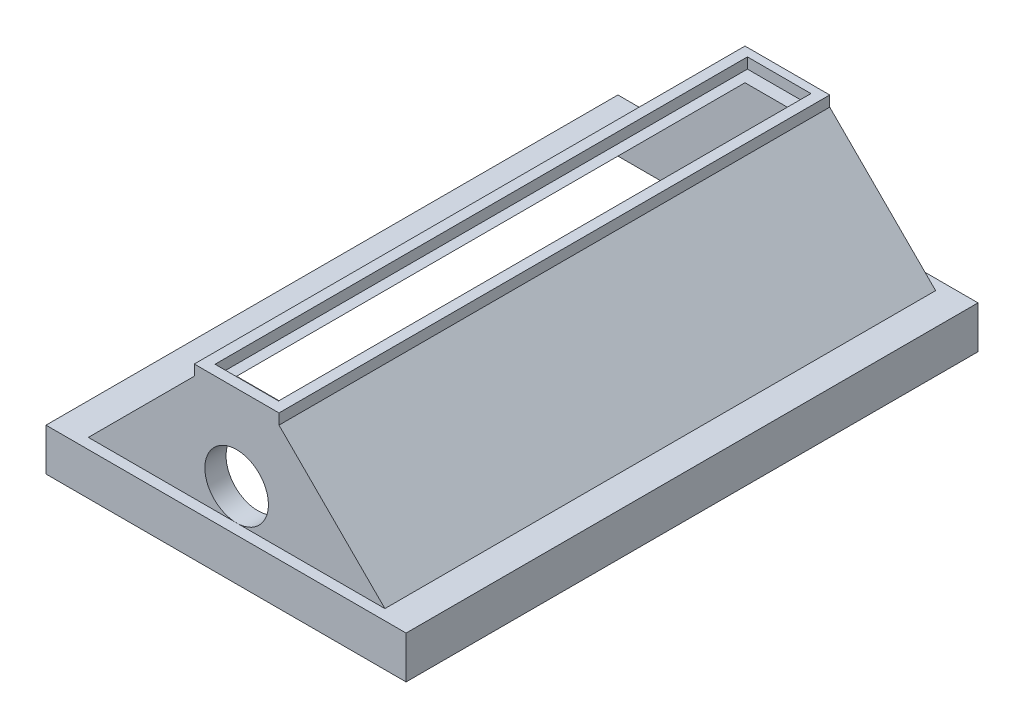
SolidWorks part; units mm, degrees
ref_plane "Front Plane" through (0, 0, 0) normal (0, 0, 1) x (1, 0, 0)
ref_plane "Top Plane" through (0, 0, 0) normal (0, 1, 0) x (1, 0, 0)
ref_plane "Right Plane" through (0, 0, 0) normal (1, 0, 0) x (0, 0, -1)
sketch "Sketch2" plane through (0, 0, 0) normal (0, 0, 1) x (1, 0, 0)
  line L0 (0, 17.5) -> (0, 21.824) construction
  line L1 (-10, 17.5) -> (10, 17.5)
  line L2 (10, 17.5) -> (40, -12.5)
  line L3 (-40, -12.5) -> (40, -12.5)
  line L7 (0, 17.5) -> (10, 17.5)
  line L8 (-10, 17.5) -> (-40, -12.5)
  circle A0 centre (0, 0) radius 7.5
  point P0 (0, 0)
  point P6 (0, 0)
  point P10 (0, 0)
  dimension "D2" = 17.5
  dimension "D1" = 30
  dimension "D3" = 10
  dimension "D4" = 80
extrude "Boss-Extrude1" add sketch "Sketch2" along normal blind 5 contours L1 L8 L3 L2 A0
sketch "Sketch5" plane through (0, 0, 0) normal (0, 0, -1) x (-1, 0, 0)
  line L0 (-40, -12.5) -> (-35, -12.5)
  line L1 (40, -12.5) -> (-40, -12.5) construction
  line L2 (-35, -12.5) -> (-5, 17.5)
  line L3 (10, 17.5) -> (-10, 17.5) construction
  line L4 (-10, 17.5) -> (-40, -12.5)
  line L5 (10, 17.5) -> (40, -12.5)
  line L6 (40, -12.5) -> (35, -12.5)
  line L7 (35, -12.5) -> (5, 17.5)
  line L8 (5, 17.5) -> (10, 17.5)
  line M5 (10, 17.5) -> (-10, 17.5)
  line M6 (-10, 17.5) -> (-40, -12.5)
  line M7 (-40, -12.5) -> (40, -12.5)
  dimension "D1" = 5
  dimension "D2" = 5
  dimension "D3" = 5
  dimension "D4" = 5
extrude "Boss-Extrude4" add sketch "Sketch5" along normal blind 120 contours L2 M7 M5 M6 | L5 L6 L7 L8
sketch "Sketch6" plane through (0, 0, -120) normal (0, 0, -1) x (-1, 0, 0)
  line L0 (-40, -12.5) -> (40, -12.5)
  line L1 (40, -12.5) -> (10, 17.5)
  line L2 (10, 17.5) -> (-10, 17.5)
  line L3 (-10, 17.5) -> (-40, -12.5)
extrude "Boss-Extrude5" add sketch "Sketch6" along normal blind 5
sketch "Sketch7" plane through (0, -12.5, 0) normal (0, -1, 0) x (-1, 0, 0)
  line L0 (-40, -5) -> (-40, 125) construction
  line L1 (-42.5, -7.5) -> (42.5, -7.5)
  line L2 (-42.5, -7.5) -> (-42.5, 127.5)
  line L3 (-42.5, 127.5) -> (42.5, 127.5)
  line L4 (42.5, -7.5) -> (42.5, 127.5)
  line L5 (40, -5) -> (40, 125) construction
  line L6 (-40, 125) -> (40, 125) construction
  line L7 (40, -5) -> (-40, -5) construction
  line L9 (-35, 0) -> (35, 0)
  line L10 (-35, 0) -> (-35, 120)
  line L11 (-35, 120) -> (35, 120)
  line L12 (35, 0) -> (35, 120)
  dimension "D1" = 2.5
  dimension "D2" = 2.5
  dimension "D3" = 2.5
  dimension "D4" = 2.5
extrude "Boss-Extrude6" add sketch "Sketch7" against normal blind 5
sketch "Sketch10" plane through (0, -12.5, 0) normal (0, -1, 0) x (-1, 0, 0)
  line L1 (42.5, 127.5) -> (-42.5, 127.5)
  line L2 (42.5, 127.5) -> (42.5, -7.5)
  line L3 (42.5, -7.5) -> (-42.5, -7.5)
  line L4 (-42.5, 127.5) -> (-42.5, -7.5)
  line L5 (40.05, 125.05) -> (-40.05, 125.05)
  line L6 (40.05, 125.05) -> (40.05, -5.05)
  line L7 (40.05, -5.05) -> (-40.05, -5.05)
  line L8 (-40.05, 125.05) -> (-40.05, -5.05)
  dimension "D1" = 2.45
  dimension "D2" = 2.45
  dimension "D3" = 2.45
  dimension "D4" = 2.45
extrude "Boss-Extrude9" add sketch "Sketch10" along normal blind 5
sketch "Sketch11" plane through (0, 17.5, 0) normal (0, 1, 0) x (1, 0, 0)
  line L0 (5, 120) -> (5, 0) construction
  line L1 (-7.5, 123.0684) -> (7.5, 123.0684)
  line L2 (-7.5, 123.0684) -> (-7.5, -2.6021)
  line L3 (-7.5, -2.6021) -> (7.5, -2.6021)
  line L4 (7.5, 123.0684) -> (7.5, -2.6021)
  line L5 (-5, 120) -> (-5, 0) construction
  line L7 (-10, 125) -> (10, 125)
  line L8 (-10, 125) -> (-10, -5)
  line L9 (-10, -5) -> (10, -5)
  line L10 (10, 125) -> (10, -5)
  dimension "D1" = 2.5
  dimension "D2" = 2.5
extrude "Boss-Extrude10" add sketch "Sketch11" along normal blind 2.5
